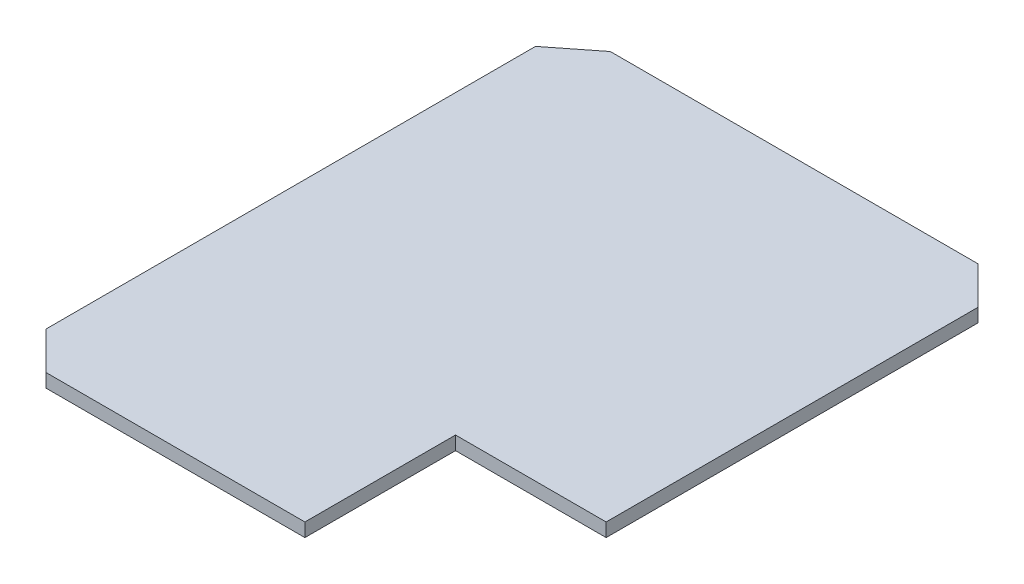
SolidWorks part; units mm, degrees
ref_plane "Front Plane" through (0, 0, 0) normal (0, 0, 1) x (1, 0, 0)
ref_plane "Top Plane" through (0, 0, 0) normal (0, 1, 0) x (1, 0, 0)
ref_plane "Right Plane" through (0, 0, 0) normal (1, 0, 0) x (0, 0, -1)
sketch "Sketch1" plane through (0, 0, 0) normal (0, 1, 0) x (1, 0, 0)
  line L10 (-197.56, 183.8578) -> (-254, 139.4078)
  line L12 (146.05, -571.7922) -> (146.05, -368.5922)
  line L13 (-203.2, -571.7922) -> (-254, -520.9922)
  line L15 (298.45, 183.8578) -> (349.25, 133.0578)
  line L16 (-197.56, 183.8578) -> (298.45, 183.8578)
  line L17 (349.25, 133.0578) -> (349.25, -368.5922)
  line L18 (146.05, -571.7922) -> (-203.2, -571.7922)
  line L19 (-254, -520.9922) -> (-254, 139.4078)
  line L20 (146.05, -368.5922) -> (349.25, -368.5922)
  dimension "D1" = 203.2
  dimension "D2" = 203.2
  dimension "D3" = 254
  dimension "D4" = 349.25
  dimension "D5" = 755.65
  dimension "D6" = 135
  dimension "D8" = 71.842
  dimension "D9" = 71.842
  dimension "D10" = 71.842
  dimension "D11" = 183.8578
  dimension "D12" = 135
extrude "Boss-Extrude1" add sketch "Sketch1" along normal blind 18.288
